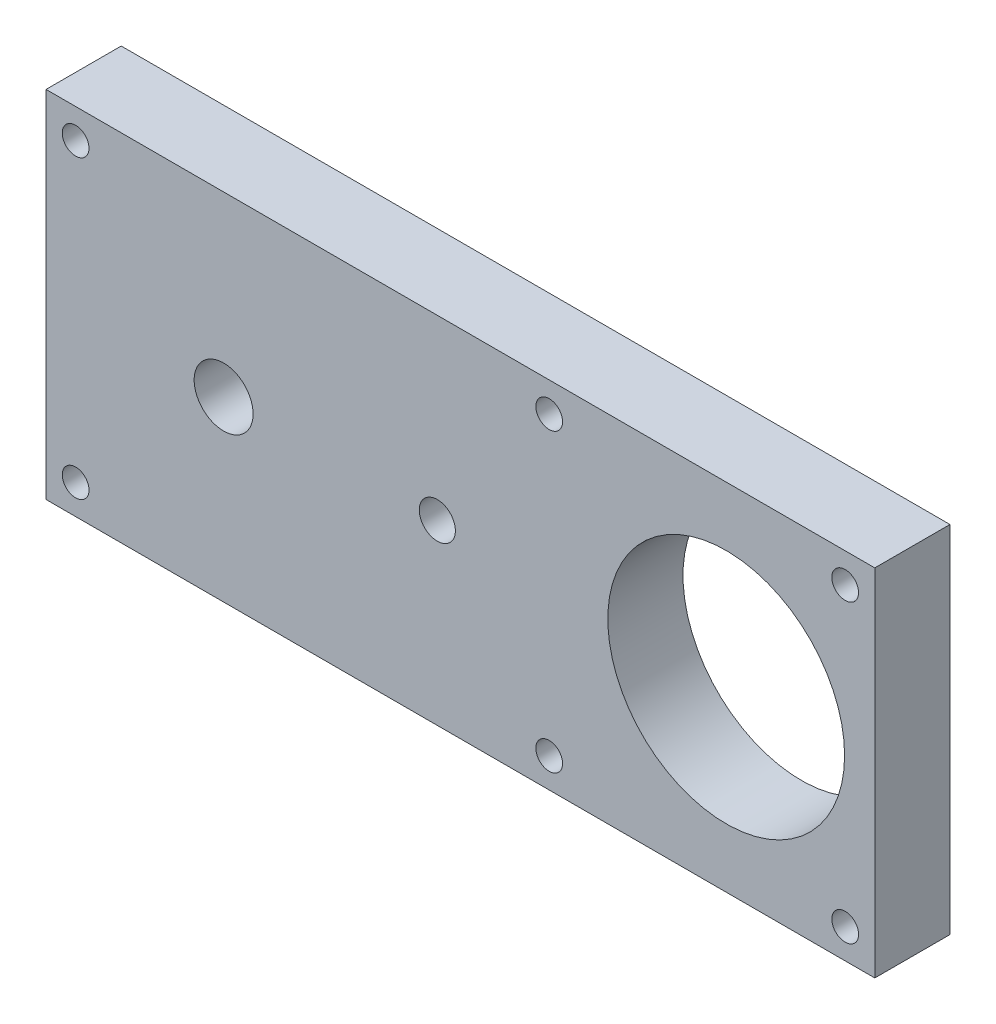
SolidWorks part; units mm, degrees
ref_plane "Front Plane" through (0, 0, 0) normal (0, 0, 1) x (1, 0, 0)
ref_plane "Top Plane" through (0, 0, 0) normal (0, 1, 0) x (1, 0, 0)
ref_plane "Right Plane" through (0, 0, 0) normal (1, 0, 0) x (0, 0, -1)
sketch "Sketch1" plane through (0, 0, 0) normal (0, 0, 1) x (1, 0, 0)
  line L1 (0, 0) -> (70, 0)
  line L2 (0, 0) -> (0, 30)
  line L3 (0, 30) -> (70, 30)
  line L4 (70, 0) -> (70, 30)
  dimension "D1" = 70
  dimension "D2" = 30
extrude "Boss-Extrude1" add sketch "Sketch1" along normal blind 6.35
hole_wizard "#2 Clearance Hole1" positions "Sketch3" profile "Sketch2" hole size "#2" standard "ANSI Inch" end condition through all
sketch "Sketch3" plane through (0, 0, 6.35) normal (0, 0, 1) x (1, 0, 0)
  line L0 (2.5, 30) -> (2.5, 0) construction
  line L1 (70, 30) -> (0, 30) construction
  line L2 (0, 0) -> (70, 0) construction
  line L4 (0, 27.5) -> (70, 27.5) construction
  line L5 (0, 30) -> (0, 0) construction
  line L6 (70, 0) -> (70, 30) construction
  line L8 (0, 15) -> (70, 15) construction
  line L11 (42.5, 30) -> (42.5, 0) construction
  line L13 (67.5, 30) -> (67.5, 0) construction
  point P30 (2.5, 27.5)
  point P32 (42.5, 27.5)
  point P34 (67.5, 27.5)
  point P38 (67.5, 2.5)
  point P39 (42.5, 2.5)
  point P40 (2.5, 2.5)
  dimension "D1" = 2.5
  dimension "D2" = 2.5
  dimension "D3" = 40
  dimension "D4" = 2.5
sketch "Sketch2" plane through (2.5, 27.5, 6.35) normal (1, 0, 0) x (0, -1, 0)
  line L0 (0, 0) -> (0, 6.35)
  line L1 (0, 6.35) -> (1.1303, 6.35)
  line L2 (1.1303, 6.35) -> (1.1303, 0)
  line L5 (1.1303, 0) -> (0, 0)
  line L11 (0, -6.35) -> (0, 107.95) construction
  dimension "Thru Hole Dia." = 2.2606
  dimension "Thru Hole Depth" = 6.35
sketch "Sketch4" plane through (0, 0, 6.35) normal (0, 0, 1) x (1, 0, 0)
  line L0 (0, 0) -> (70, 0) construction
  line L1 (70, 0) -> (70, 30) construction
  line L2 (70, 15) -> (0, 15) construction
  line L3 (0, 30) -> (0, 0) construction
  circle A0 centre (57.45, 15) radius 10
  circle A1 centre (15, 15) radius 2.4892
  circle A2 centre (33.05, 15) radius 1.525
  dimension "D1" = 20
  dimension "D4" = 4.9784
  dimension "D6" = 3.05
  dimension "D2" = 15
  dimension "D3" = 12.55
  dimension "D5" = 15
  dimension "D7" = 33.05
extrude "Cut-Extrude1" cut sketch "Sketch4" against normal through all
